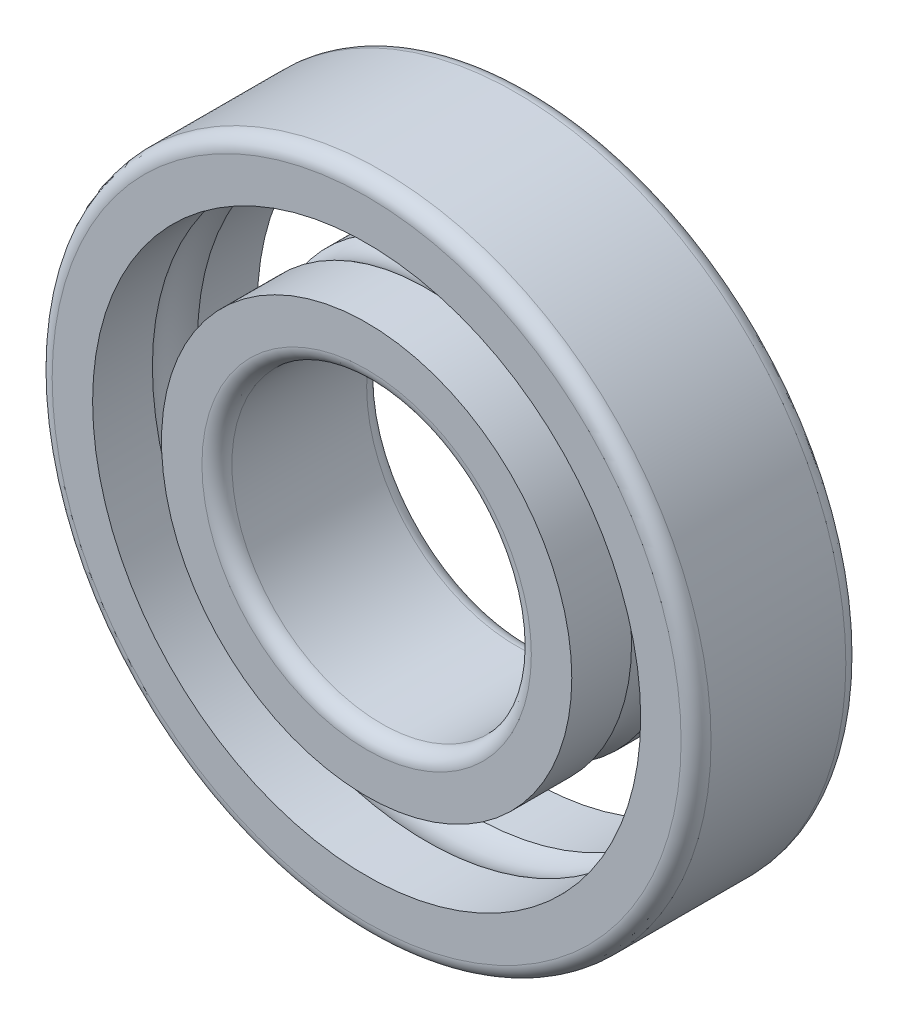
SolidWorks part; units mm, degrees
material "1.4511 (X3CrNb17)"
ref_plane "前视基准面" through (0, 0, 0) normal (0, 0, 1) x (1, 0, 0)
ref_plane "上视基准面" through (0, 0, 0) normal (0, 1, 0) x (1, 0, 0)
ref_plane "右视基准面" through (0, 0, 0) normal (1, 0, 0) x (0, 0, -1)
sketch "草图1" plane through (0, 0, 0) normal (0, 1, 0) x (1, 0, 0)
  line L0 (13.7, 6) -> (13.7, 2.0075)
  line L5 (10, 6) -> (13.7, 6)
  line L6 (10, 6) -> (10, -5)
  line L7 (10, -5) -> (13.7, -5)
  line L8 (22, 6) -> (22, -5)
  line L9 (10, 6) -> (22, -5) construction
  line L10 (10, -5) -> (22, 6) construction
  line L11 (18.3, 6) -> (18.3, 2.0075)
  line L12 (13.7, -1.0075) -> (13.7, -5)
  line L13 (18.3, -1.0075) -> (18.3, -5)
  line L14 (18.3, 6) -> (22, 6)
  line L15 (18.3, -5) -> (22, -5)
  line L16 (0, -14.2702) -> (0, 18.4944) construction
  arc A0 (13.7, 2.0075) -> (13.7, -1.0075) centre (16, 0.5) ccw
  arc A1 (18.3, -1.0075) -> (18.3, 2.0075) centre (16, 0.5) ccw
  point P0 (16, 0.5)
  dimension "D5" = 5.5
  dimension "D1" = 12
  dimension "D2" = 11
  dimension "D3" = 10
  dimension "D4" = 5
  dimension "D6" = 3.7
  dimension "D7" = 3.7
revolve "旋转1" add sketch "草图1" angle 360 about L16
fillet "圆角1" radius 1 2 edges at (22, 0, -6) (22, 0, 5)
fillet "圆角2" radius 1 2 edges at (10, 0, -6) (10, 0, 5)
